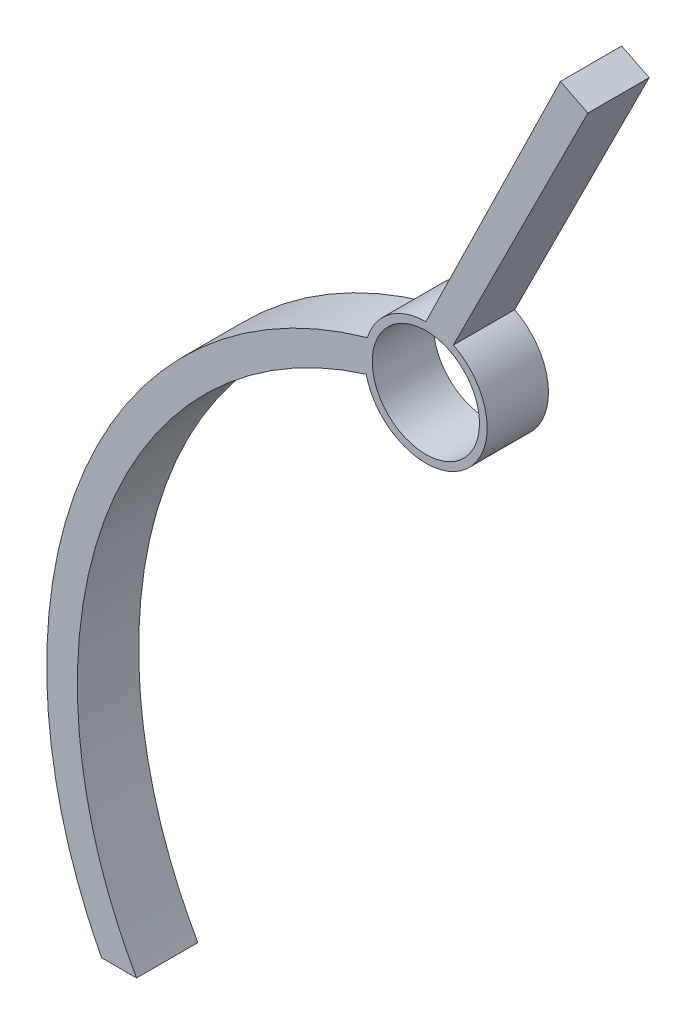
SolidWorks part; units mm, degrees
ref_plane "Alzado" through (0, 0, 0) normal (0, 0, 1) x (1, 0, 0)
ref_plane "Planta" through (0, 0, 0) normal (0, 1, 0) x (1, 0, 0)
ref_plane "Vista lateral" through (0, 0, 0) normal (1, 0, 0) x (0, 0, -1)
sketch "Croquis1" plane through (0, 0, 0) normal (0, 0, 1) x (1, 0, 0)
  line L0 (-32.6176, 278.3437) -> (73.0628, 489.0742)
  line L1 (73.0628, 489.0742) -> (55.185, 498.0398)
  line L2 (55.185, 498.0398) -> (-32.6176, 318.3437)
  line L3 (-244.1544, -146.8625) -> (244.1544, -146.8625)
  circle A0 centre (-32.6176, 278.3437) radius 40
  circle A1 centre (-32.6176, 278.3437) radius 35
  ellipse E0 centre (0, 0) end of major axis (0, -300) minor radius 280
  ellipse E1 centre (0, 0) end of major axis (0, 280) minor radius 260
  dimension "D1" = 280
  dimension "D5" = 80
  dimension "D6" = 70
  dimension "D2" = 300
  dimension "D3" = 280
  dimension "D4" = 260
  dimension "D7" = 20
  dimension "D8" = 488.3087
  dimension "D9" = 146.8625
  dimension "D10" = 200
extrude "Saliente-Extruir15" add sketch "Croquis1" along normal blind 40 contours E1 A0 E0 L3 | E1 A1 E0 A0 | E0 A1 L0 A0 | A1 E1 A0 | E1 A0 E0 A1 | E0 A0 L0 A1 | A0 L0 L1 L2
sketch "Croquis2" plane through (0, 0, 0) normal (0, 0, 1) x (1, 0, 0)
  circle A0 centre (-255.4205, 87.2345) radius 4
